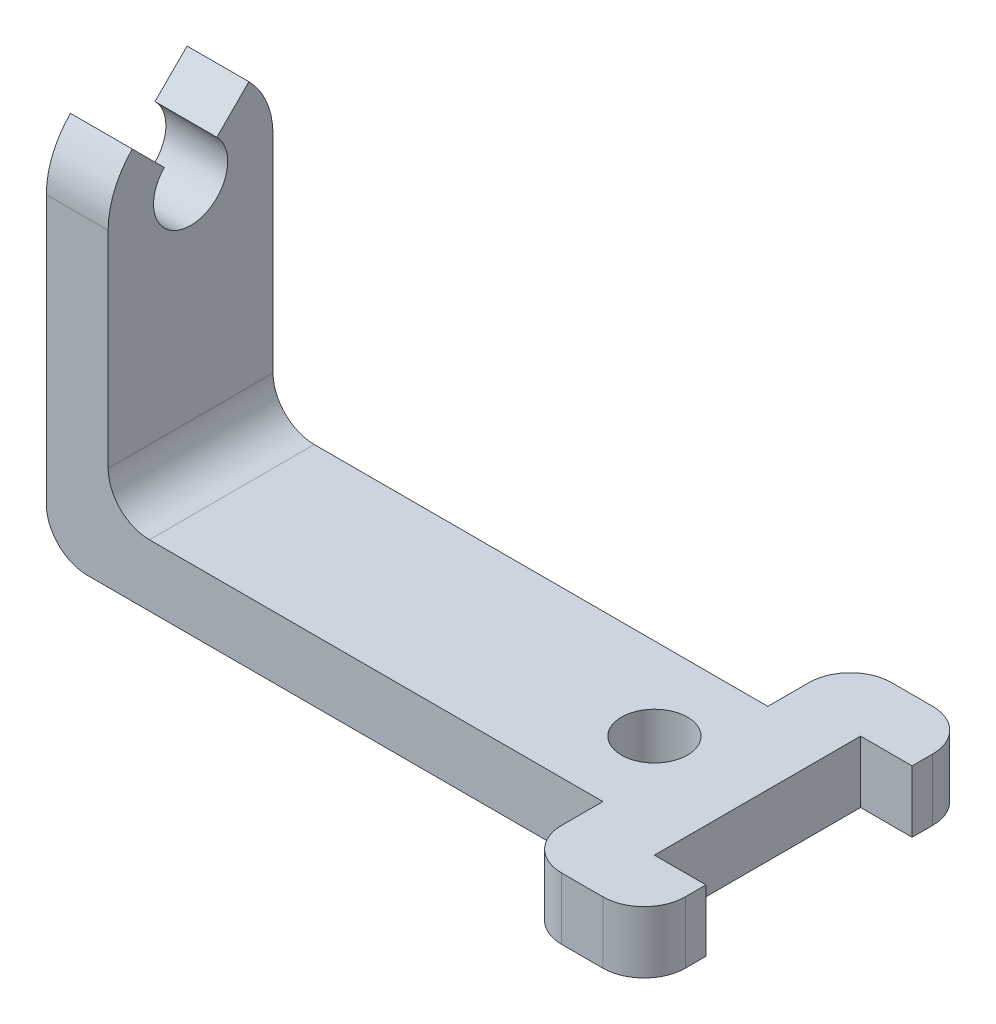
SolidWorks part; units mm, degrees
ref_plane "前视基准面" through (0, 0, 0) normal (0, 0, 1) x (1, 0, 0)
ref_plane "上视基准面" through (0, 0, 0) normal (0, 1, 0) x (1, 0, 0)
ref_plane "右视基准面" through (0, 0, 0) normal (1, 0, 0) x (0, 0, -1)
other "Configuration Table"
sketch "草图1" plane through (0, 0, 0) normal (0, 1, 0) x (1, 0, 0)
  line L0 (-20.2348, 0) -> (24.1711, 0) construction
  line L4 (-14.5, -4) -> (-14.5, 4)
  line L5 (12.5, -3) -> (-12.5, 3) construction
  line L6 (12.5, 3) -> (-12.5, -3) construction
  line L7 (18.5, -8) -> (18.5, -5)
  line L8 (18.5, 8) -> (12.5, 8)
  line L10 (18.5, -8) -> (12.5, -8)
  line L12 (18.5, 5) -> (18.5, 8)
  line L13 (16, -5) -> (18.5, -5)
  line L14 (16, -5) -> (16, 5)
  line L15 (16, 5) -> (18.5, 5)
  line L17 (16, -5) -> (21, 5) construction
  line L18 (16, 5) -> (21, -5) construction
  line L20 (-14.5, -4) -> (12.5, -4)
  line L21 (-14.5, 4) -> (12.5, 4)
  line L23 (12.5, 8) -> (12.5, 4)
  line L24 (12.5, -4) -> (12.5, -8)
  circle A0 centre (11, 0) radius 1.6
  point P0 (0, 0)
  point P12 (20.3291, 0)
  point P13 (18.5, 0)
  dimension "D9" = 3.2
  dimension "D10" = 5
  dimension "D1" = 6
  dimension "D2" = 6
  dimension "D3" = 10
  dimension "D4" = 2.5
  dimension "D5" = 16
  dimension "D6" = 25
  dimension "D7" = 4
  dimension "D8" = 4
  dimension "D11" = 27
extrude "凸台-拉伸1" add sketch "草图1" along normal blind 3
sketch "草图3" plane through (-14.5, 0, 0) normal (-1, 0, 0) x (0, 0, 1)
  line L1 (-4, 15) -> (-4, 3)
  line L3 (4, 3) -> (4, 15)
  line L6 (-1.2728, 16.2728) -> (-2.8284, 17.8284)
  line L7 (1.2728, 16.2728) -> (2.8284, 17.8284)
  line L8 (-1.2728, 16.2728) -> (0, 15) construction
  line L9 (-4, 3) -> (4, 3)
  line L10 (0, 9.1237) -> (0, 19.7019) construction
  line L11 (0, 15) -> (1.2728, 16.2728) construction
  arc A3 (4, 15) -> (2.8284, 17.8284) centre (0, 15) ccw
  arc A4 (-1.2728, 16.2728) -> (1.2728, 16.2728) centre (0, 15) ccw
  arc A5 (-2.8284, 17.8284) -> (-4, 15) centre (0, 15) ccw
  dimension "D1" = 3.6
  dimension "D3" = 12
  dimension "D4" = 4
  dimension "D5" = 45
extrude "凸台-拉伸2" add sketch "草图3" against normal blind 3
fillet "圆角1" radius 2 4 edges at (12.5, 1.5, -8) (12.5, 1.5, 8) (18.5, 1.5, -8) (18.5, 1.5, 8)
fillet "圆角2" radius 2 2 edges at (-11.5, 3, 0) (-14.5, 0, 0)
